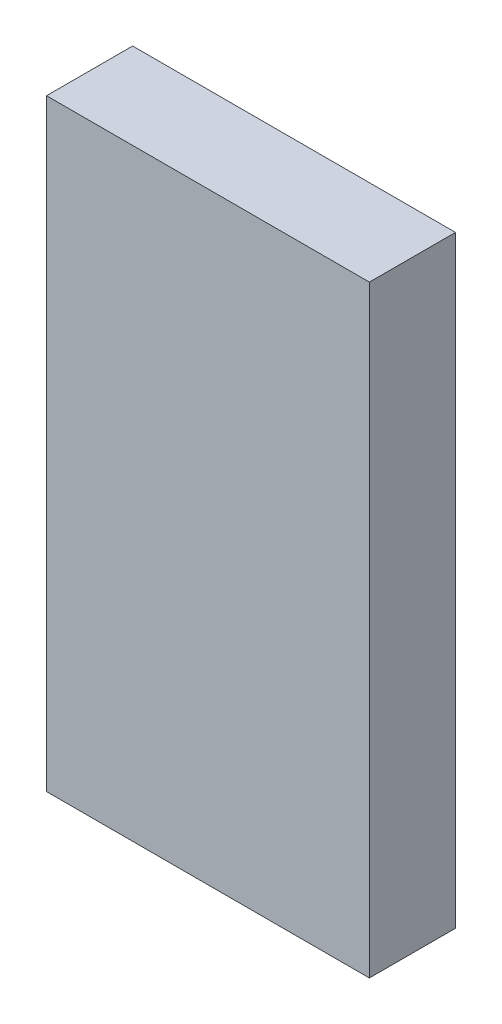
SolidWorks part; units mm, degrees
ref_plane "Front Plane" through (0, 0, 0) normal (0, 0, 1) x (1, 0, 0)
ref_plane "Top Plane" through (0, 0, 0) normal (0, 1, 0) x (1, 0, 0)
ref_plane "Right Plane" through (0, 0, 0) normal (1, 0, 0) x (0, 0, -1)
sketch3d "3DSketch1"
  line L1 (433.0131, 1132.3876, 249.224) -> (283.0131, 1132.3876, 249.224)
  line L2 (433.0131, 1132.3876, 249.224) -> (433.0131, 852.3876, 249.224)
  line L3 (433.0131, 852.3876, 249.224) -> (283.0131, 852.3876, 249.224)
  line L4 (283.0131, 1132.3876, 249.224) -> (283.0131, 852.3876, 249.224)
  line L5 (433.0131, 1132.3876, 249.224) -> (283.0131, 852.3876, 249.224) construction
  line L6 (433.0131, 852.3876, 249.224) -> (283.0131, 1132.3876, 249.224) construction
  point P0 (358.0131, 992.3876, 249.224)
  dimension "D1" = 280
  dimension "D2" = 150
extrude "Boss-Extrude1" add sketch "3DSketch1" along a picked direction on the side of the normal blind 40
